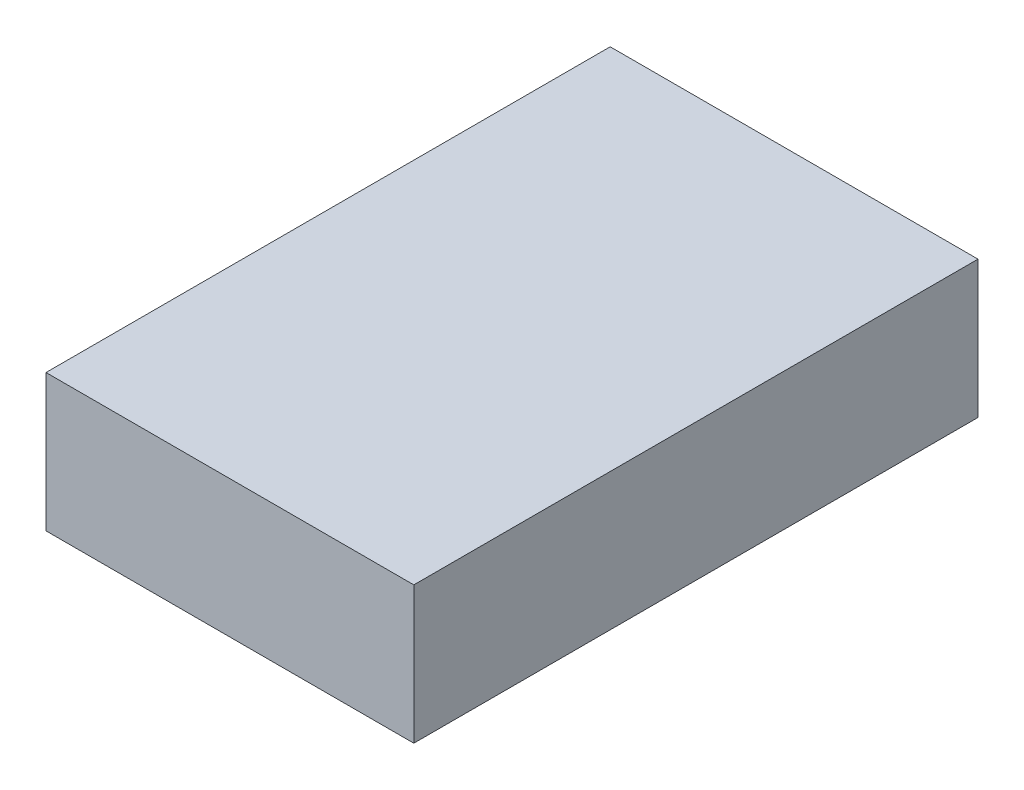
SolidWorks part; units mm, degrees
ref_plane "前基準面" through (0, 0, 0) normal (0, 0, 1) x (1, 0, 0)
ref_plane "上基準面" through (0, 0, 0) normal (0, 1, 0) x (1, 0, 0)
ref_plane "右基準面" through (0, 0, 0) normal (1, 0, 0) x (0, 0, -1)
sketch "草圖1" plane through (0, 0, 0) normal (0, 0, 1) x (1, 0, 0)
  line L1 (-49.7576, 48.5929) -> (9.2424, 48.5929)
  line L2 (-49.7576, 48.5929) -> (-49.7576, 26.5929)
  line L3 (-49.7576, 26.5929) -> (9.2424, 26.5929)
  line L4 (9.2424, 48.5929) -> (9.2424, 26.5929)
  dimension "D1" = 59
  dimension "D2" = 22
extrude "填料-伸長1" add sketch "草圖1" along normal blind 90.5
